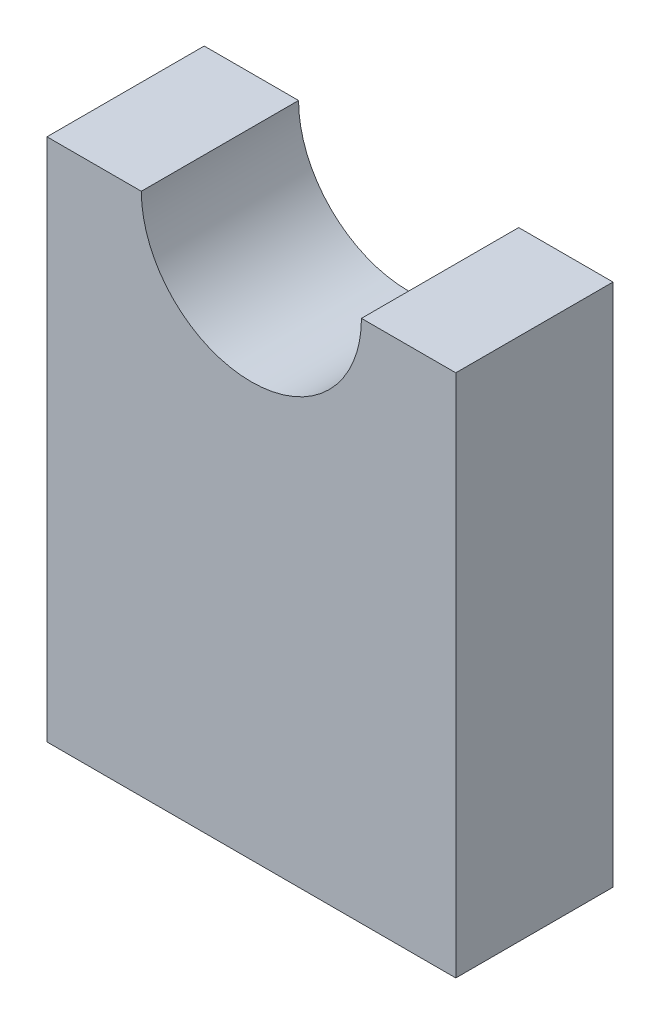
SolidWorks part; units mm, degrees
ref_plane "前视基准面" through (0, 0, 0) normal (0, 0, 1) x (1, 0, 0)
ref_plane "上视基准面" through (0, 0, 0) normal (0, 1, 0) x (1, 0, 0)
ref_plane "右视基准面" through (0, 0, 0) normal (1, 0, 0) x (0, 0, -1)
other "Configuration Table"
sketch "草图1" plane through (0, 0, 0) normal (0, 1, 0) x (1, 0, 0)
  line L1 (-39, 15) -> (39, 15)
  line L2 (-39, 15) -> (-39, -15)
  line L3 (-39, -15) -> (39, -15)
  line L4 (39, 15) -> (39, -15)
  line L5 (-39, 15) -> (39, -15) construction
  line L6 (-39, -15) -> (39, 15) construction
  point P0 (0, 0)
extrude "凸台-拉伸1" add sketch "草图1" along normal blind 100
sketch "草图2" plane through (0, 0, 0) normal (0, 0, 1) x (1, 0, 0)
  line L0 (0, 0) -> (0, 100) construction
  line L1 (-39, 100) -> (39, 100) construction
  circle A0 centre (0, 100) radius 21
extrude "切除-拉伸1" cut sketch "草图2" against normal through all both and the other way through all
